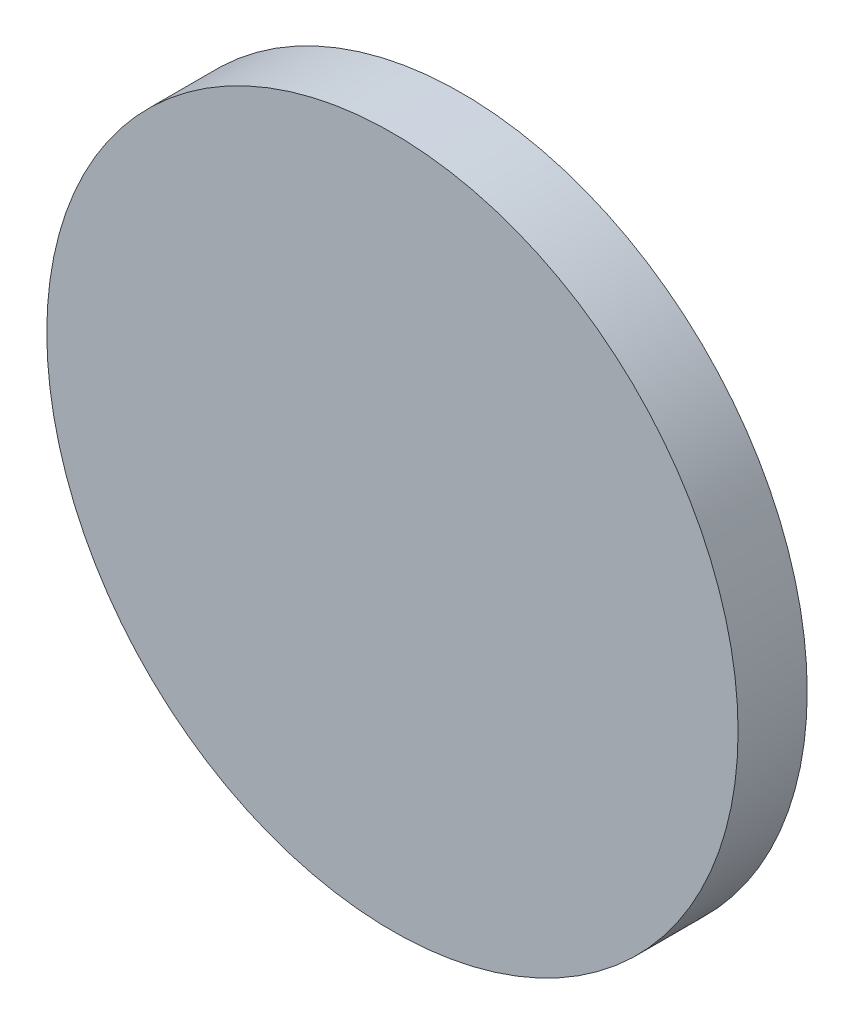
SolidWorks part; units mm, degrees
ref_plane "Front Plane" through (0, 0, 0) normal (0, 0, 1) x (1, 0, 0)
ref_plane "Top Plane" through (0, 0, 0) normal (0, 1, 0) x (1, 0, 0)
ref_plane "Right Plane" through (0, 0, 0) normal (1, 0, 0) x (0, 0, -1)
sketch "Sketch1" plane through (0, 0, 0) normal (0, 0, 1) x (1, 0, 0)
  circle A0 centre (-62.3906, -116) radius 7.5
extrude "Boss-Extrude1" add sketch "Sketch1" against normal blind 1.5
